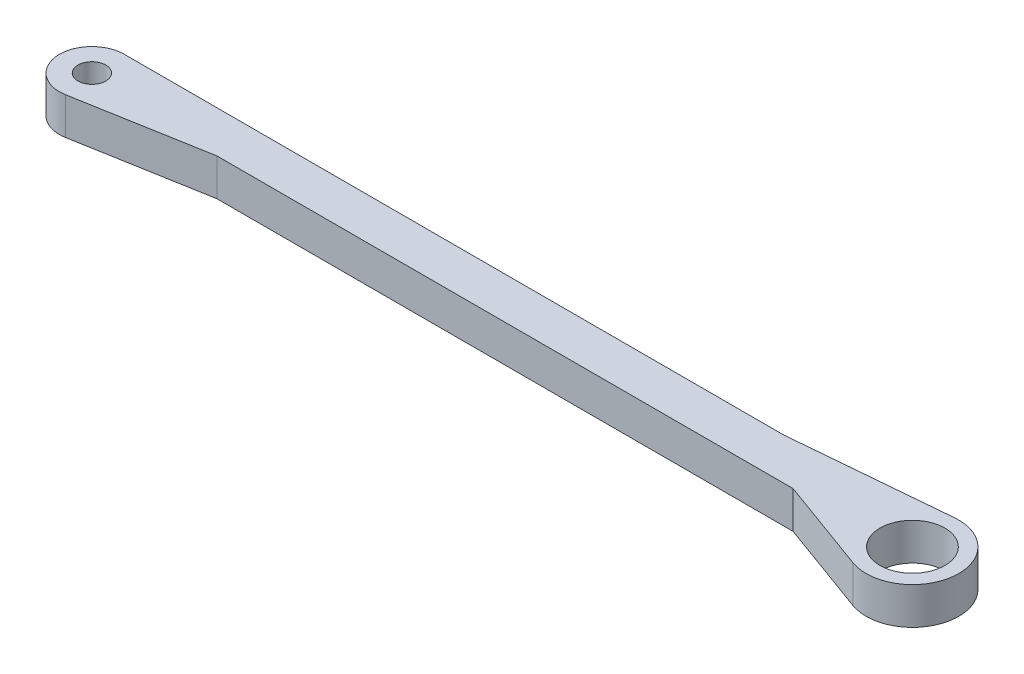
SolidWorks part; units mm, degrees
ref_plane "前视基准面" through (0, 0, 0) normal (0, 0, 1) x (1, 0, 0)
ref_plane "上视基准面" through (0, 0, 0) normal (0, 1, 0) x (1, 0, 0)
ref_plane "右视基准面" through (0, 0, 0) normal (1, 0, 0) x (0, 0, -1)
other "Configuration Table"
sketch "草图1" plane through (0, 0, 0) normal (0, 1, 0) x (1, 0, 0)
  line L0 (0, 0) -> (177, 0) construction
  line L1 (0, 7) -> (169.8586, 7)
  line L2 (6.7082, -2) -> (167.202, -2)
  line L3 (28.9688, -2) -> (1.2155, -6.8937)
  line L4 (173.5798, -9.3969) -> (153.2569, -2)
  line L5 (176.1284, 9.9619) -> (142.2732, 7)
  circle A0 centre (0, 0) radius 3
  circle A1 centre (0, 0) radius 7
  circle A2 centre (177, 0) radius 7
  circle A3 centre (177, 0) radius 10
  dimension "D1" = 6
  dimension "D2" = 14
  dimension "D4" = 20
  dimension "D5" = 14
  dimension "D3" = 177
  dimension "D6" = 7
  dimension "D7" = 2
  dimension "D8" = 10
  dimension "D9" = 20
  dimension "D10" = 5
extrude "凸台-拉伸2" add sketch "草图1" along normal blind 8
